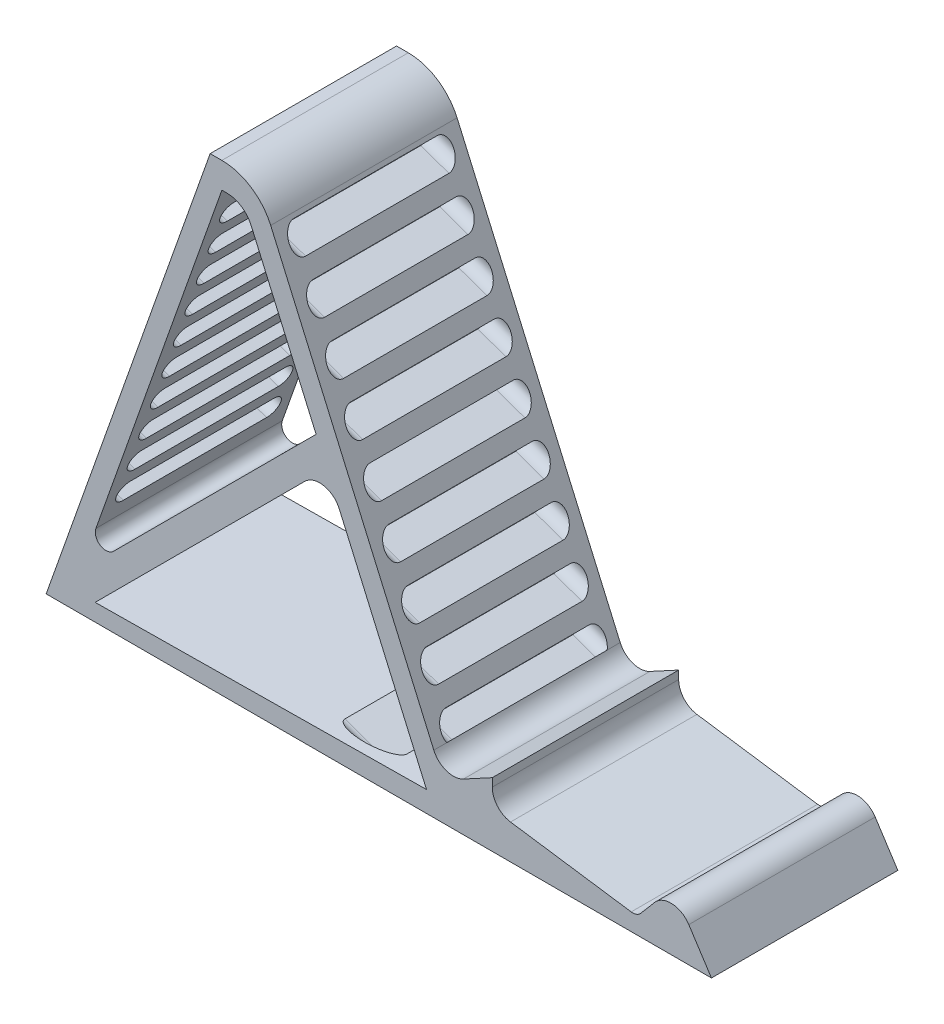
SolidWorks part; units mm, degrees
ref_plane "Front Plane" through (0, 0, 0) normal (0, 0, 1) x (1, 0, 0)
ref_plane "Top Plane" through (0, 0, 0) normal (0, 1, 0) x (1, 0, 0)
ref_plane "Right Plane" through (0, 0, 0) normal (1, 0, 0) x (0, 0, -1)
sketch "Sketch1" plane through (0, 0, 0) normal (0, 0, 1) x (1, 0, 0)
  line L0 (3.8256, 2.0717) -> (9.2331, 5)
  line L1 (-23.6067, 0) -> (70.2891, 0) construction
  line L2 (-1.7438, 3.9858) -> (-32.3786, 74.0082)
  line L3 (9.2331, 5) -> (9.2331, 3.4616)
  line L4 (-43.7433, 80) -> (-74.5418, -7)
  line L5 (-43.7433, 80) -> (-41.5402, 80)
  line L6 (22.2333, -16.6098) -> (-32.9712, 75.155) construction
  line L7 (23.812, -3.9425) -> (42.7459, -3.9425) construction
  line L8 (37.1287, -3.0998) -> (39.7352, -0.0336)
  line L9 (36.4123, -3.9425) -> (-18.0639, 42.3673) construction
  line L10 (12.6589, -0.4969) -> (35.3178, -3.7837)
  line L11 (-74.5418, -7) -> (50.3939, -7)
  line L12 (50.3939, -7) -> (46.1375, -0.4458)
  line L13 (-41.5402, 75.155) -> (-65.1965, 8.3301)
  line L14 (-65.3422, -3.7794) -> (-3.1156, -3.1027)
  line L15 (-36.0426, 72.159) -> (-23.8516, 44.2939)
  line L16 (-41.5402, 75.155) -> (-40.6234, 75.155)
  line L17 (-61.897, 6.2485) -> (-23.8516, 44.2939)
  line L18 (-65.3422, -3.7794) -> (-25.9922, 35.5706)
  line L19 (-19.4992, 34.3455) -> (-3.1156, -3.1027)
  arc A0 (-32.3786, 74.0082) -> (-41.5402, 80) centre (-41.5402, 70) ccw
  arc A1 (3.8256, 2.0717) -> (-1.7438, 3.9858) centre (1.9209, 5.5891) cw
  arc A2 (9.2331, 3.4616) -> (12.6589, -0.4969) centre (13.2331, 3.4616) ccw
  arc A3 (39.7352, -0.0336) -> (46.1375, -0.4458) centre (42.7828, -2.6243) cw
  arc A4 (37.1287, -3.0998) -> (35.3178, -3.7837) centre (35.6049, -1.8044) cw
  arc A5 (-36.0426, 72.159) -> (-40.6234, 75.155) centre (-40.6234, 70.155) ccw
  arc A6 (-61.897, 6.2485) -> (-65.1965, 8.3301) centre (-63.3112, 7.6627) cw
  arc A7 (-25.9922, 35.5706) -> (-19.4992, 34.3455) centre (-23.1638, 32.7422) cw
  point P10 (-35, 80)
  point P21 (0, 0)
  point P24 (9.2331, 0)
  point P28 (43.213, 4.0575)
  point P45 (-21.8482, 39.7147)
  dimension "D6" = 10
  dimension "D9" = 71.5
  dimension "D10" = 4
  dimension "D11" = 4
  dimension "D12" = 4
  dimension "D13" = 2
  dimension "D14" = 5
  dimension "D15" = 2
  dimension "D16" = 4
  dimension "D1" = 10.5
  dimension "D2" = 5
  dimension "D3" = 80
  dimension "D4" = 35
  dimension "D5" = 7
  dimension "D7" = 10.5
  dimension "D8" = 8
extrude "Boss-Extrude1" add sketch "Sketch1" along normal blind 35
sketch "Sketch3" plane through (-64.0384, 22.67, 0) normal (-0.9427, 0.3337, 0) x (0, 0, 1)
  line L0 (17.5, 60.8163) -> (17.5, -45.1091) construction
  line L1 (35, 60.8163) -> (0, 60.8163) construction
  line L2 (4.0444, 56.3819) -> (30.9556, 56.3819) construction
  line L3 (4.0444, 58.3861) -> (30.9556, 58.3861)
  line L4 (4.0444, 54.3777) -> (30.9556, 54.3777)
  line L5 (4.0444, 49.8819) -> (30.9556, 49.8819) construction
  line L6 (4.0444, 51.8861) -> (30.9556, 51.8861)
  line L7 (4.0444, 47.8777) -> (30.9556, 47.8777)
  line L8 (4.0444, 43.3819) -> (30.9556, 43.3819) construction
  line L9 (4.0444, 45.3861) -> (30.9556, 45.3861)
  line L10 (4.0444, 41.3777) -> (30.9556, 41.3777)
  line L11 (4.0444, 36.8819) -> (30.9556, 36.8819) construction
  line L12 (4.0444, 38.8861) -> (30.9556, 38.8861)
  line L13 (4.0444, 34.8777) -> (30.9556, 34.8777)
  line L14 (4.0444, 30.3819) -> (30.9556, 30.3819) construction
  line L15 (4.0444, 32.3861) -> (30.9556, 32.3861)
  line L16 (4.0444, 28.3777) -> (30.9556, 28.3777)
  line L17 (4.0444, 23.8819) -> (30.9556, 23.8819) construction
  line L18 (4.0444, 25.8861) -> (30.9556, 25.8861)
  line L19 (4.0444, 21.8777) -> (30.9556, 21.8777)
  line L20 (4.0444, 17.3819) -> (30.9556, 17.3819) construction
  line L21 (4.0444, 19.3861) -> (30.9556, 19.3861)
  line L22 (4.0444, 15.3777) -> (30.9556, 15.3777)
  line L23 (4.0444, 10.8819) -> (30.9556, 10.8819) construction
  line L24 (4.0444, 12.8861) -> (30.9556, 12.8861)
  line L25 (4.0444, 8.8777) -> (30.9556, 8.8777)
  line L26 (4.0444, 4.3819) -> (30.9556, 4.3819) construction
  line L27 (4.0444, 6.3861) -> (30.9556, 6.3861)
  line L28 (4.0444, 2.3777) -> (30.9556, 2.3777)
  line L29 (4.0444, -2.1181) -> (30.9556, -2.1181) construction
  line L30 (4.0444, -0.1139) -> (30.9556, -0.1139)
  line L31 (4.0444, -4.1223) -> (30.9556, -4.1223)
  line L32 (4.0444, -8.6181) -> (30.9556, -8.6181) construction
  line L33 (4.0444, -6.6139) -> (30.9556, -6.6139)
  line L34 (4.0444, -10.6223) -> (30.9556, -10.6223)
  arc A0 (4.0444, 58.3861) -> (4.0444, 54.3777) centre (4.0444, 56.3819) ccw
  arc A1 (30.9556, 54.3777) -> (30.9556, 58.3861) centre (30.9556, 56.3819) ccw
  arc A2 (4.0444, 51.8861) -> (4.0444, 47.8777) centre (4.0444, 49.8819) ccw
  arc A3 (30.9556, 47.8777) -> (30.9556, 51.8861) centre (30.9556, 49.8819) ccw
  arc A4 (4.0444, 45.3861) -> (4.0444, 41.3777) centre (4.0444, 43.3819) ccw
  arc A5 (30.9556, 41.3777) -> (30.9556, 45.3861) centre (30.9556, 43.3819) ccw
  arc A6 (4.0444, 38.8861) -> (4.0444, 34.8777) centre (4.0444, 36.8819) ccw
  arc A7 (30.9556, 34.8777) -> (30.9556, 38.8861) centre (30.9556, 36.8819) ccw
  arc A8 (4.0444, 32.3861) -> (4.0444, 28.3777) centre (4.0444, 30.3819) ccw
  arc A9 (30.9556, 28.3777) -> (30.9556, 32.3861) centre (30.9556, 30.3819) ccw
  arc A10 (4.0444, 25.8861) -> (4.0444, 21.8777) centre (4.0444, 23.8819) ccw
  arc A11 (30.9556, 21.8777) -> (30.9556, 25.8861) centre (30.9556, 23.8819) ccw
  arc A12 (4.0444, 19.3861) -> (4.0444, 15.3777) centre (4.0444, 17.3819) ccw
  arc A13 (30.9556, 15.3777) -> (30.9556, 19.3861) centre (30.9556, 17.3819) ccw
  arc A14 (4.0444, 12.8861) -> (4.0444, 8.8777) centre (4.0444, 10.8819) ccw
  arc A15 (30.9556, 8.8777) -> (30.9556, 12.8861) centre (30.9556, 10.8819) ccw
  arc A16 (4.0444, 6.3861) -> (4.0444, 2.3777) centre (4.0444, 4.3819) ccw
  arc A17 (30.9556, 2.3777) -> (30.9556, 6.3861) centre (30.9556, 4.3819) ccw
  arc A18 (4.0444, -0.1139) -> (4.0444, -4.1223) centre (4.0444, -2.1181) ccw
  arc A19 (30.9556, -4.1223) -> (30.9556, -0.1139) centre (30.9556, -2.1181) ccw
  arc A20 (4.0444, -6.6139) -> (4.0444, -10.6223) centre (4.0444, -8.6181) ccw
  arc A21 (30.9556, -10.6223) -> (30.9556, -6.6139) centre (30.9556, -8.6181) ccw
  point P6 (17.5, 56.3819)
  point P15 (17.5, 49.8819)
  point P22 (17.5, 43.3819)
  point P29 (17.5, 36.8819)
  point P36 (17.5, 30.3819)
  point P43 (17.5, 23.8819)
  point P50 (17.5, 17.3819)
  point P57 (17.5, 10.8819)
  point P64 (17.5, 4.3819)
  point P71 (17.5, -2.1181)
  point P78 (17.5, -8.6181)
  dimension "D1" = 4.0084
  dimension "D2" = 26.9111
  dimension "D3" = 11
extrude "Cut-Extrude4" cut sketch "Sketch3" against normal up to surface (13.2507 mm away)
